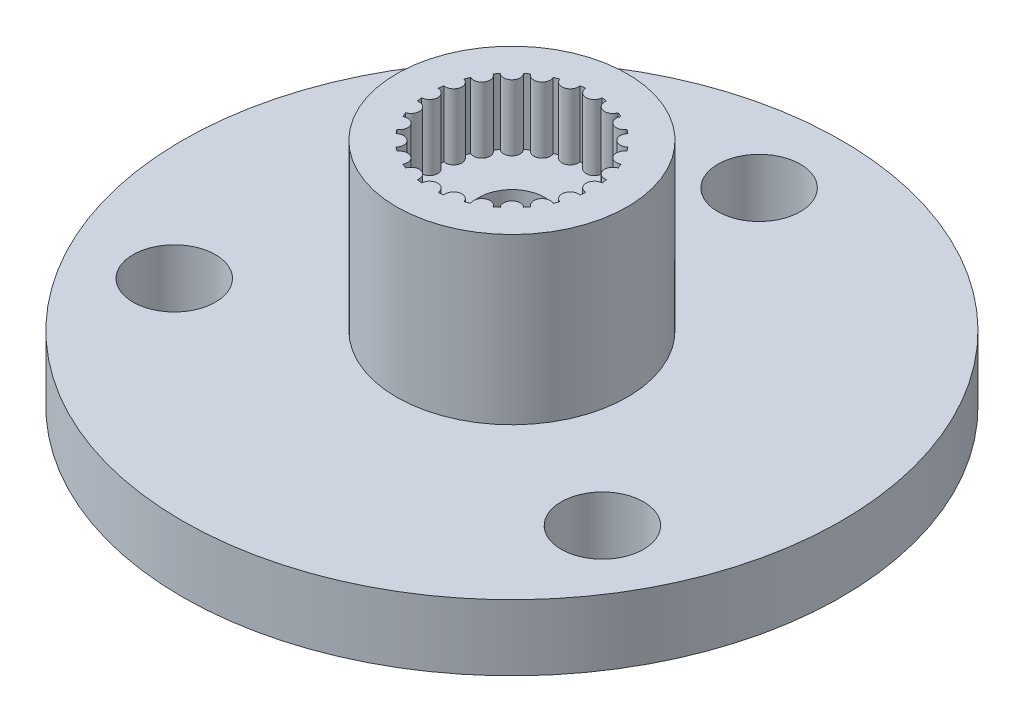
SolidWorks part; units mm, degrees
ref_plane "Front Plane" through (0, 0, 0) normal (0, 0, 1) x (1, 0, 0)
ref_plane "Top Plane" through (0, 0, 0) normal (0, 1, 0) x (1, 0, 0)
ref_plane "Right Plane" through (0, 0, 0) normal (1, 0, 0) x (0, 0, -1)
sketch "Sketch1" plane through (0, 0, 0) normal (0, 1, 0) x (1, 0, 0)
  circle A0 centre (0, 0) radius 10
  circle A1 centre (0, 0) radius 1
  dimension "D1" = 20
  dimension "D2" = 2
extrude "Boss-Extrude1" add sketch "Sketch1" along normal blind 2
sketch "Sketch2" plane through (0, 2, 0) normal (0, 1, 0) x (1, 0, 0)
  circle A0 centre (0, 0) radius 3.5
  circle A1 centre (0, 0) radius 2.5
  dimension "D1" = 7
  dimension "D2" = 5
extrude "Boss-Extrude2" add sketch "Sketch2" along normal blind 5
sketch "Sketch3" plane through (0, 2, 0) normal (0, 1, 0) x (1, 0, 0)
  line L0 (0, 0) -> (0, 4.3743) construction
  line L1 (0, 7.5) -> (0, 10) construction
  circle A0 centre (0, 7.5) radius 1.25
  circle A2 centre (0, 0) radius 10 construction
  dimension "D1" = 2.5
  dimension "D2" = 2.5
extrude "Cut-Extrude1" cut sketch "Sketch3" against normal up to next
pattern_circular "CirPattern1" count 3 over 360 about axis through (0, 0, 0) along (0, 1, 0) of "Cut-Extrude1"
sketch "Sketch4" plane through (0, 2, 0) normal (0, 1, 0) x (1, 0, 0)
  circle A0 centre (0, 0) radius 1
  circle A1 centre (0, 0) radius 2.5
  circle A2 centre (0, 0) radius 2.5 construction
  circle A3 centre (0, 0) radius 1 construction
extrude "Boss-Extrude3" add sketch "Sketch4" along normal offset from surface (3 mm away) 2 up to face at (0, 7, 3.5)
sketch "Sketch5" plane through (0, 0, 0) normal (0, -1, 0) x (1, 0, 0)
  circle A0 centre (0, 0) radius 2
  dimension "D1" = 4
extrude "Cut-Extrude2" cut sketch "Sketch5" against normal offset from surface (4 mm away) 1 up to face at (0, 5, 1)
sketch "Sketch6" plane through (0, 7, 0) normal (0, 1, 0) x (1, 0, 0)
  line L0 (0, 0) -> (0, 2.5) construction
  arc A0 (-0.2497, 2.4875) -> (0.2497, 2.4875) centre (0, 2.5) ccw
  circle A1 centre (0, 0) radius 2.5 construction
  circle A2 centre (0, 0) radius 2.5 construction
  arc A3 (0.2497, 2.4875) -> (-0.2497, 2.4875) centre (0, 0) ccw
  dimension "D1" = 0.5
extrude "Boss-Extrude4" add sketch "Sketch6" against normal up to surface (2 mm away) up to face at (0, 5, 1)
pattern_circular "CirPattern2" count 24 over 360 about axis through (0, 0, 0) along (0, 1, 0) of "Boss-Extrude4"
